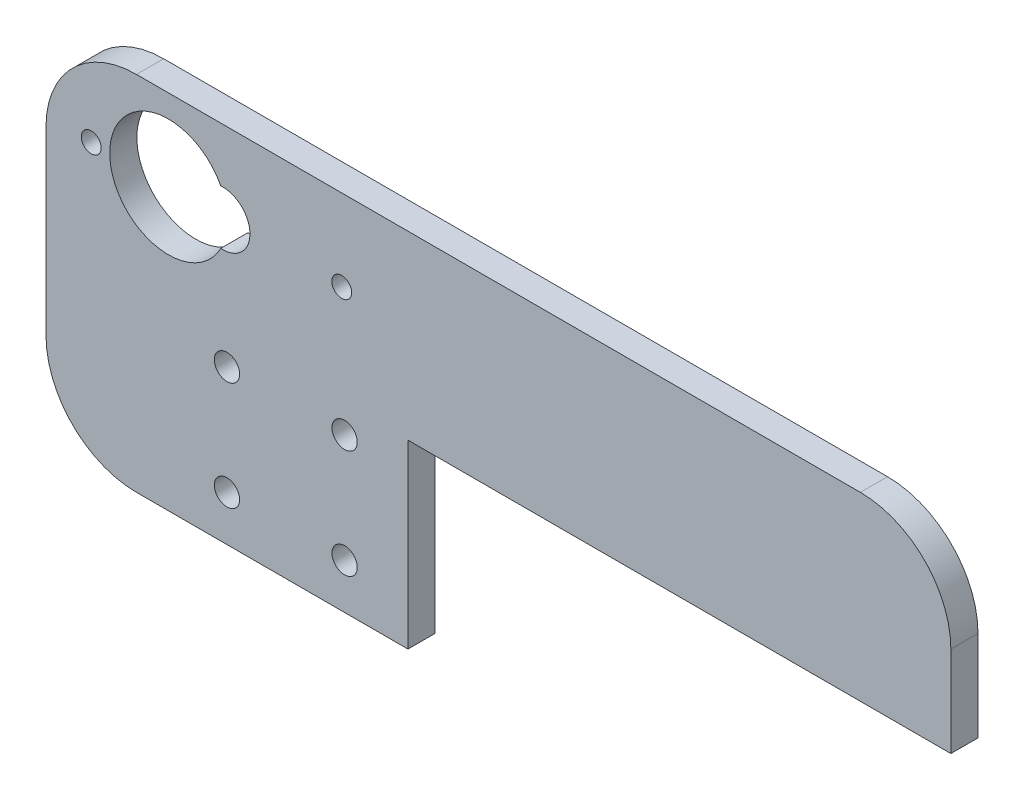
SolidWorks part; units mm, degrees
ref_plane "前视基准面" through (0, 0, 0) normal (0, 0, 1) x (1, 0, 0)
ref_plane "上视基准面" through (0, 0, 0) normal (0, 1, 0) x (1, 0, 0)
ref_plane "右视基准面" through (0, 0, 0) normal (1, 0, 0) x (0, 0, -1)
sketch "草图1" plane through (0, 0, 0) normal (0, 0, 1) x (1, 0, 0)
  line L1 (0, 0) -> (100, 0)
  line L2 (0, 0) -> (0, 40)
  line L3 (0, 40) -> (100, 40)
  line L4 (100, 0) -> (100, 40)
  dimension "D1" = 40
  dimension "D2" = 100
extrude "凸台-拉伸1" add sketch "草图1" along normal blind 3
sketch "草图6" plane through (0, 0, 0) normal (0, 0, -1) x (-1, 0, 0)
  line L0 (-100, 5) -> (0, 5) construction
  line L1 (-100, 0) -> (-100, 40) construction
  line L2 (0, 40) -> (0, 0) construction
  line L3 (0, 0) -> (-100, 0) construction
  line L4 (-100, 17) -> (0, 17) construction
  circle A0 centre (-20, 5) radius 1.4
  circle A1 centre (-20, 17) radius 1.4
  circle A2 centre (-33, 17) radius 1.4
  circle A3 centre (-33, 5) radius 1.4
  dimension "D3" = 2.8
  dimension "D4" = 13
  dimension "D5" = 13
  dimension "D6" = 20
  dimension "D7" = 20
  dimension "D1" = 5
  dimension "D2" = 12
extrude "切除-拉伸4" cut sketch "草图6" against normal blind 3
sketch "草图7" plane through (0, 0, 3) normal (0, 0, 1) x (1, 0, 0)
  line L1 (100, 0) -> (40, 0)
  line L2 (100, 0) -> (100, 20)
  line L3 (100, 20) -> (40, 20)
  line L4 (40, 0) -> (40, 20)
  dimension "D1" = 20
  dimension "D2" = 60
extrude "切除-拉伸5" cut sketch "草图7" against normal blind 3
sketch "草图8" plane through (0, 0, 3) normal (0, 0, 1) x (1, 0, 0)
  line L0 (33, 17) -> (33, 5) construction
  line L1 (33, 11) -> (0, 11) construction
  line L2 (0, 31) -> (100, 31) construction
  line L5 (0, 40) -> (0, 0) construction
  circle A0 centre (5, 31) radius 1.1
  circle A1 centre (13.54, 31) radius 6.5
  circle A2 centre (19.54, 31) radius 3
  circle A3 centre (32.68, 31) radius 1.1
  dimension "D2" = 2.2
  dimension "D3" = 13
  dimension "D4" = 6
  dimension "D9" = 2.2
  dimension "D1" = 20
  dimension "D5" = 6
  dimension "D6" = 19.14
  dimension "D7" = 5
  dimension "D8" = 8.54
extrude "切除-拉伸6" cut sketch "草图8" against normal blind 3 contours A2 A1 | A1 A2 | A1 A2 | A0 | A3
fillet "圆角1" radius 10 3 edges at (0, 0, 1.5) (100, 40, 1.5) (0, 40, 1.5)
